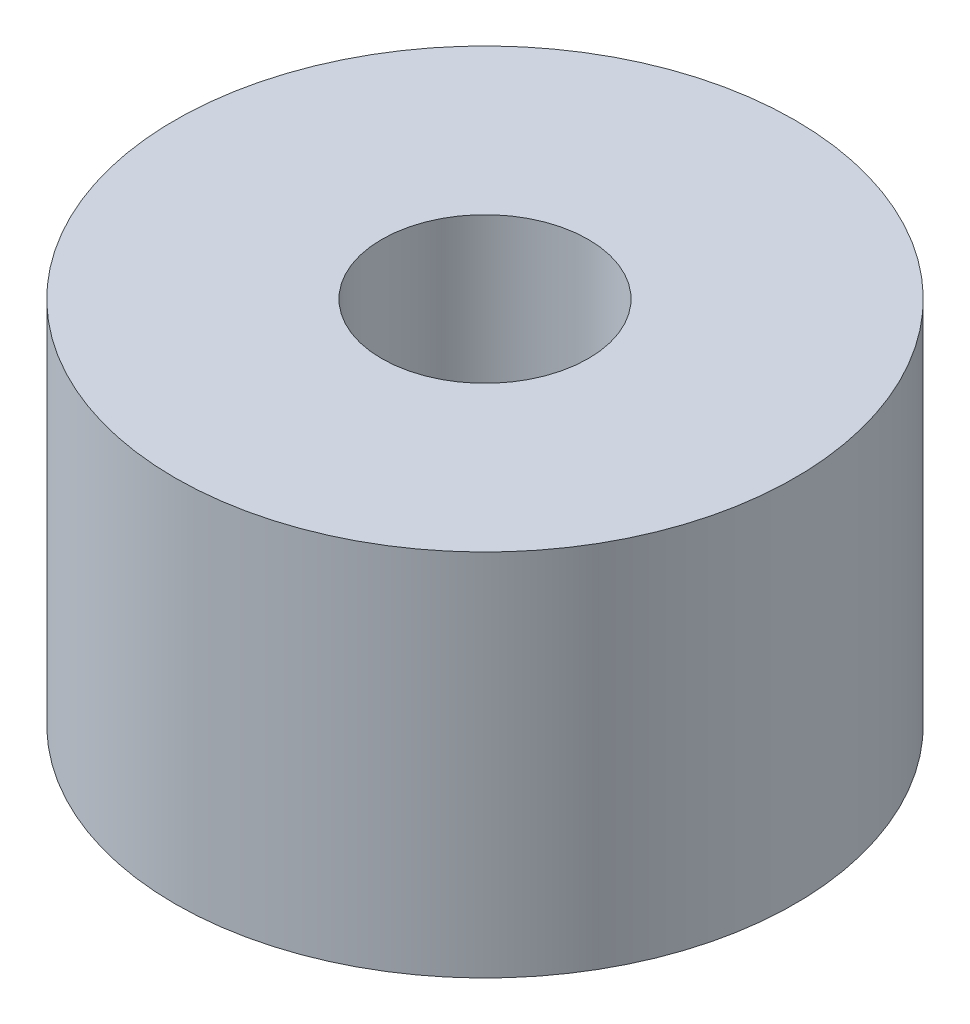
SolidWorks part; units mm, degrees
ref_plane "Front Plane" through (0, 0, 0) normal (0, 0, 1) x (1, 0, 0)
ref_plane "Top Plane" through (0, 0, 0) normal (0, 1, 0) x (1, 0, 0)
ref_plane "Right Plane" through (0, 0, 0) normal (1, 0, 0) x (0, 0, -1)
sketch "RevolveSketch" plane through (0, 0, 0) normal (0, 0, 1) x (1, 0, 0)
  line L1 (9, -8) -> (23, -8)
  line L2 (9, -8) -> (9, 17)
  line L3 (9, 17) -> (23, 17)
  line L4 (23, -8) -> (23, 17)
  line L5 (2, -13) -> (2, 24) construction
revolve "OrdinaryBossRevolve" add sketch "RevolveSketch" angle 360 about L5
